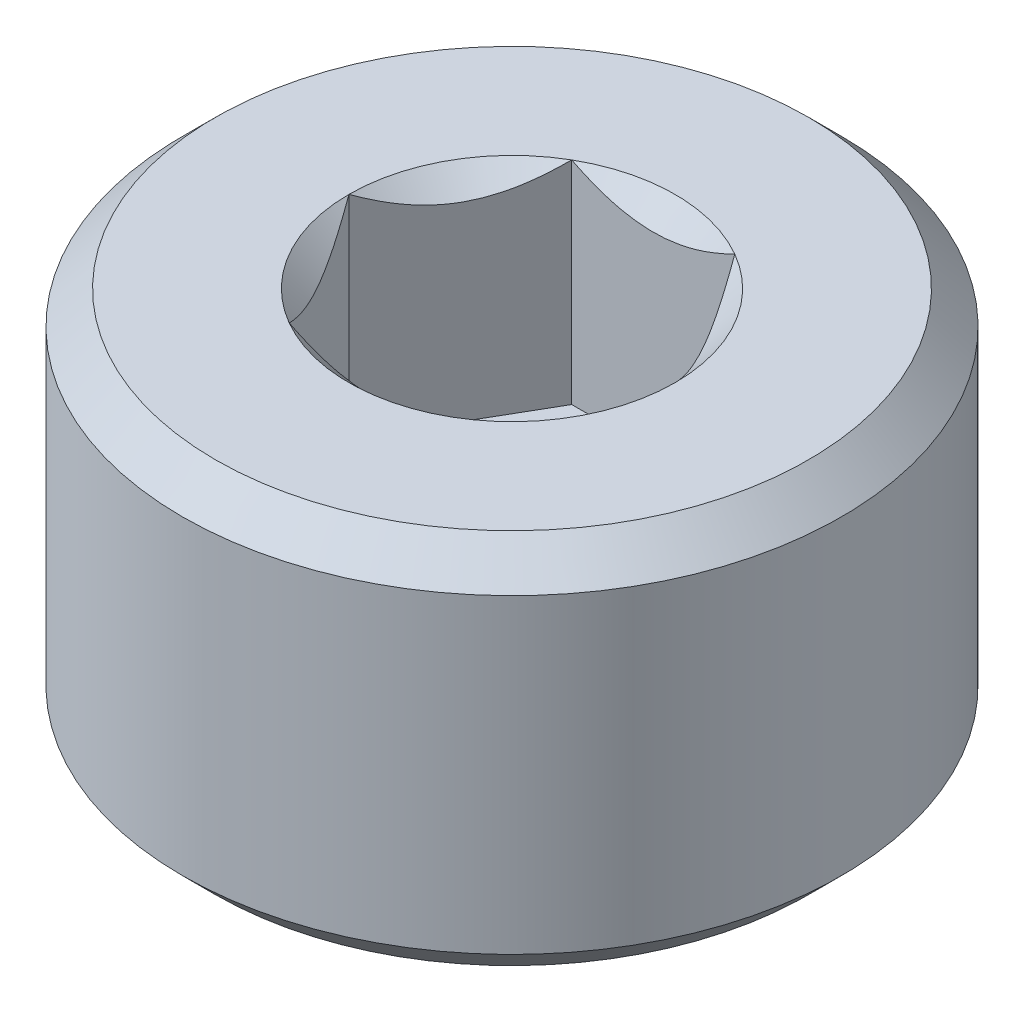
SolidWorks part; units mm, degrees
ref_plane "Front" through (0, 0, 0) normal (0, 0, 1) x (1, 0, 0)
ref_plane "Top" through (0, 0, 0) normal (0, 1, 0) x (1, 0, 0)
ref_plane "Right" through (0, 0, 0) normal (1, 0, 0) x (0, 0, -1)
sketch "Sketch1" plane through (0, 0, 0) normal (0, 1, 0) x (1, 0, 0)
  circle A0 centre (0, 0) radius 3.5
  dimension "D1" = 7
extrude "Boss-Extrude1" add sketch "Sketch1" along normal blind 4
sketch "Sketch2" plane through (0, 4, 0) normal (0, 1, 0) x (1, 0, 0)
  line L1 (0.866, 1.5) -> (-0.866, 1.5)
  line L2 (-0.866, 1.5) -> (-1.7321, 0)
  line L3 (-1.7321, 0) -> (-0.866, -1.5)
  line L4 (-0.866, -1.5) -> (0.866, -1.5)
  line L5 (0.866, -1.5) -> (1.7321, 0)
  line L6 (1.7321, 0) -> (0.866, 1.5)
  circle A0 centre (0, 0) radius 1.5 construction
  point P1 (0, 0)
  point P10 (0, 1.5)
  dimension "D1" = 3
extrude "Cut-Extrude1" cut sketch "Sketch2" against normal blind 2.25
sketch "Sketch3" plane through (0, 4, 0) normal (0, 1, 0) x (1, 0, 0)
  circle A0 centre (0, 0) radius 1.7321
extrude "Cut-Extrude2" cut sketch "Sketch3" against normal through all draft 45
chamfer "Chamfer1" distance 0.35 angle 45 2 edges at (0, 0, 3.5) (0, 4, 3.5)
